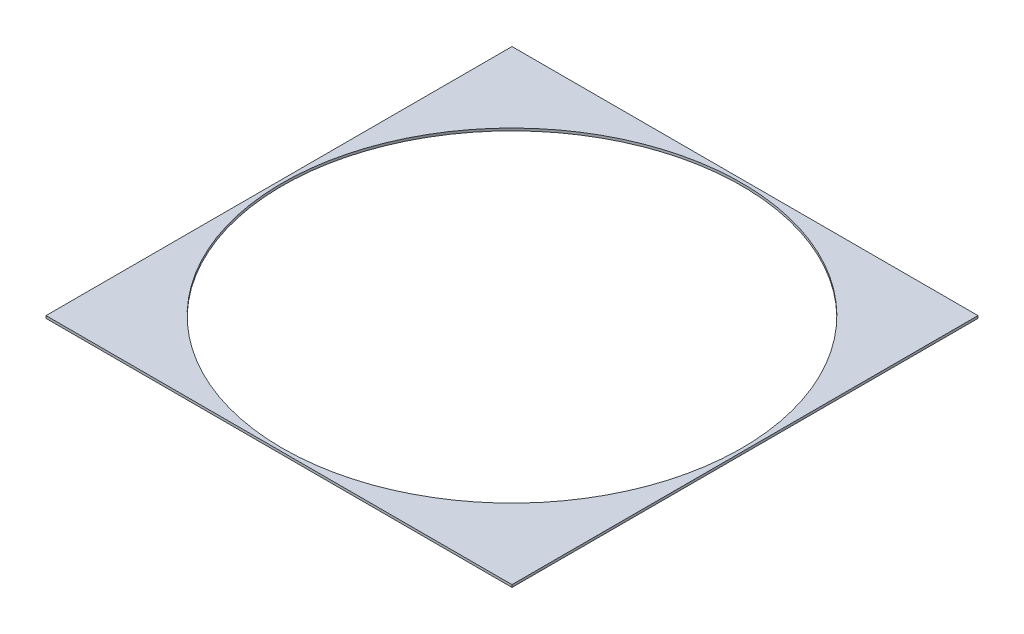
SolidWorks part; units mm, degrees
ref_plane "Front Plane" through (0, 0, 0) normal (0, 0, 1) x (1, 0, 0)
ref_plane "Top Plane" through (0, 0, 0) normal (0, 1, 0) x (1, 0, 0)
ref_plane "Right Plane" through (0, 0, 0) normal (1, 0, 0) x (0, 0, -1)
sketch "Sketch1" plane through (0, 0, 0) normal (0, 1, 0) x (1, 0, 0)
  line L1 (-142, -142) -> (142, -142)
  line L2 (-142, -142) -> (-142, 142)
  line L3 (-142, 142) -> (142, 142)
  line L4 (142, -142) -> (142, 142)
  line L5 (-142, -142) -> (142, 142) construction
  line L6 (-142, 142) -> (142, -142) construction
  circle A0 centre (0, 0) radius 140
  point P0 (0, 0)
  dimension "D3" = 280
  dimension "D1" = 284
  dimension "D2" = 284
extrude "Boss-Extrude1" add sketch "Sketch1" along normal blind 1.5 contours A0 L2 L1 | A0 L3 L2 | A0 L4 L3 | A0 L1 L4
